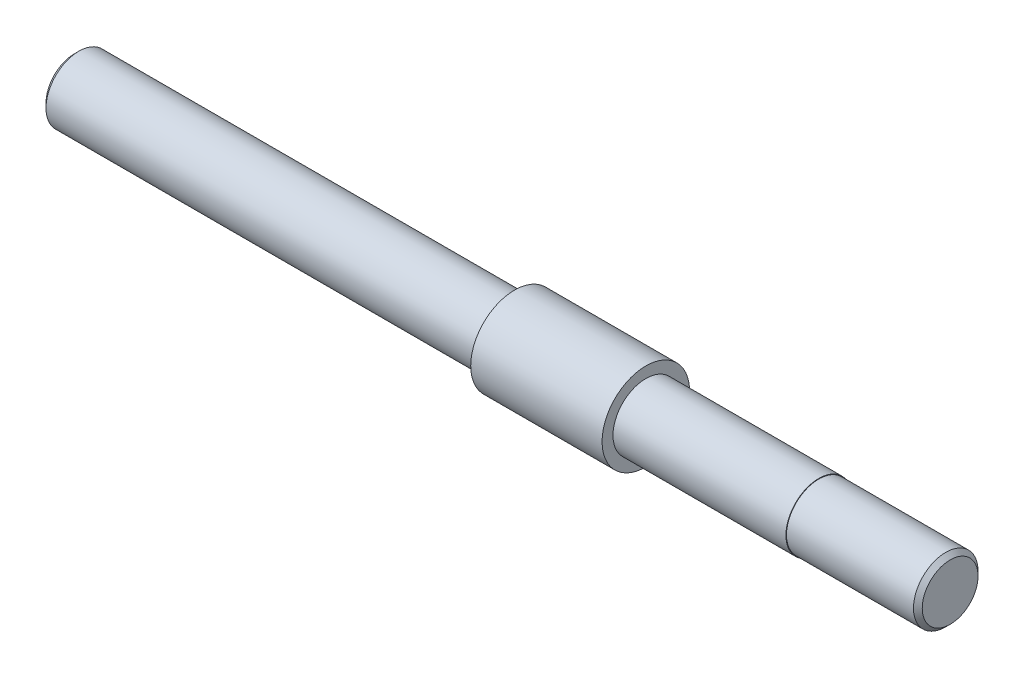
SolidWorks part; units mm, degrees
ref_plane "前视基准面" through (0, 0, 0) normal (0, 0, 1) x (1, 0, 0)
ref_plane "上视基准面" through (0, 0, 0) normal (0, 1, 0) x (1, 0, 0)
ref_plane "右视基准面" through (0, 0, 0) normal (1, 0, 0) x (0, 0, -1)
sketch "草图1" plane through (0, 0, 0) normal (0, 0, 1) x (1, 0, 0)
  line L0 (-12.0888, 0) -> (5.2383, 0) construction
  line L1 (0, 9.0788) -> (0, -9.2095) construction
  line L2 (0, 0) -> (0, 1.475)
  line L3 (0, 1.475) -> (-6, 1.475)
  line L4 (-6, 1.475) -> (-6, 1.5)
  line L5 (-6, 1.5) -> (-13.9, 1.5)
  line L6 (-13.9, 1.5) -> (-13.9, 2)
  line L7 (-13.9, 2) -> (-19.9, 2)
  line L8 (-19.9, 2) -> (-19.9, 1.5)
  line L9 (-19.9, 1.5) -> (-40, 1.5)
  line L10 (-40, 1.5) -> (-40, 0)
  line L11 (-40, 0) -> (0, 0)
  dimension "D1" = 2.95
  dimension "D2" = 3
  dimension "D3" = 3
  dimension "D4" = 4
  dimension "D5" = 6
  dimension "D6" = 13.9
  dimension "D7" = 40
  dimension "D8" = 6
revolve "旋转1" add sketch "草图1" angle 360 about L0
cosmetic thread "装饰螺纹线1" parameters "D2"=2.013
chamfer "倒角1" distance 0.2 angle 45 2 edges at (-40, 0, 1.5) (0, 0, 1.475)
